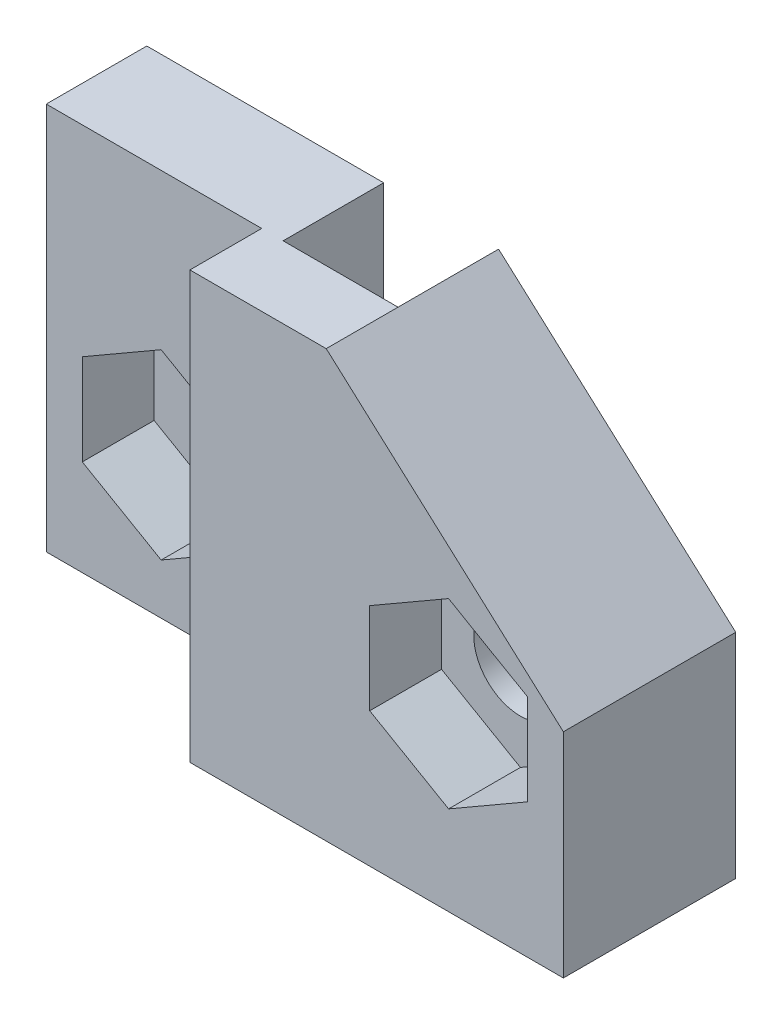
SolidWorks part; units mm, degrees
ref_plane "Alzado" through (0, 0, 0) normal (0, 0, 1) x (1, 0, 0)
ref_plane "Planta" through (0, 0, 0) normal (0, 1, 0) x (1, 0, 0)
ref_plane "Vista lateral" through (0, 0, 0) normal (1, 0, 0) x (0, 0, -1)
sketch "Croquis1" plane through (0, 0, 0) normal (0, 0, 1) x (1, 0, 0)
  line L0 (168.7324, -66.6486) -> (161.2324, -66.6486)
  line L1 (88.7324, -66.6486) -> (168.7324, -66.6486) construction
  line L2 (168.7324, -66.6486) -> (168.7324, -80.1486)
  line L4 (161.2324, -80.1486) -> (161.2324, -66.6486)
  line L5 (168.7324, -80.1486) -> (168.7324, -81.4936)
  line L7 (161.2324, -80.1486) -> (167.3874, -80.1486)
  line L8 (168.7324, -81.4936) -> (167.3874, -80.1486)
  circle A0 centre (165.2324, -75.2236) radius 1.5
  dimension "D1" = 3
  dimension "D2" = 161.2324
  dimension "D3" = 167.3874
  dimension "D4" = 81.4936
extrude "Saliente-Extruir1" add sketch "Croquis1" along normal blind 3.5
sketch "Croquis3" plane through (0, 0, 3.5) normal (0, 0, 1) x (1, 0, 0)
  line L1 (168.7324, -81.4936) -> (181.7324, -81.4936)
  line L2 (181.7324, -81.4936) -> (181.7324, -74.0711)
  line L3 (168.7324, -66.6486) -> (168.7324, -81.4936)
  line L4 (168.7324, -66.6486) -> (169.4777, -66.6486)
  line L5 (173.4777, -66.6486) -> (181.7324, -74.0711)
  line L7 (173.4777, -75.2236) -> (169.4777, -75.2236)
  line L8 (173.4777, -75.2236) -> (173.4777, -66.6486)
  line L9 (169.4777, -75.2236) -> (169.4777, -66.6486)
  line L10 (161.2324, -66.6486) -> (161.2324, -80.1486) construction
  line L11 (168.7324, -66.6486) -> (161.2324, -66.6486) construction
  circle A0 centre (177.7371, -75.2236) radius 1.625
  dimension "D1" = 3.25
  dimension "D2" = 8.2453
  dimension "D3" = 12.2453
  dimension "D4" = 16.5047
  dimension "D5" = 20.5
  dimension "D6" = 7.4225
  dimension "D7" = 8.575
extrude "Saliente-Extruir2" add sketch "Croquis3" along normal blind 2.5 and the other way blind 3.5
sketch "Croquis4" plane through (0, 0, 6) normal (0, 0, 1) x (1, 0, 0)
  line L9 (177.7371, -78.3936) -> (180.4824, -76.8086)
  line L10 (180.4824, -76.8086) -> (180.4824, -73.6386)
  line L11 (180.4824, -73.6386) -> (177.7371, -72.0536)
  line L12 (177.7371, -72.0536) -> (174.9918, -73.6386)
  line L13 (174.9918, -73.6386) -> (174.9918, -76.8086)
  line L14 (174.9918, -76.8086) -> (177.7371, -78.3936)
  circle A0 centre (177.7371, -75.2236) radius 2.7453 construction
  dimension "D1" = 5.4906
extrude "Cortar-Extruir1" cut sketch "Croquis4" against normal blind 2.5
sketch "Croquis5" plane through (0, 0, 3.5) normal (0, 0, 1) x (1, 0, 0)
  line L1 (165.2324, -78.3936) -> (167.9777, -76.8086)
  line L2 (167.9777, -76.8086) -> (167.9777, -73.6386)
  line L3 (167.9777, -73.6386) -> (165.2324, -72.0536)
  line L4 (165.2324, -72.0536) -> (162.4871, -73.6386)
  line L5 (162.4871, -73.6386) -> (162.4871, -76.8086)
  line L6 (162.4871, -76.8086) -> (165.2324, -78.3936)
  circle A0 centre (165.2324, -75.2236) radius 2.7453 construction
  dimension "D1" = 5.4906
extrude "Cortar-Extruir2" cut sketch "Croquis5" against normal blind 2.5
sketch "Croquis6" plane through (0, 0, 6) normal (0, 0, 1) x (1, 0, 0)
  line L1 (169.4777, -66.6486) -> (173.4777, -66.6486)
  line L2 (169.4777, -66.6486) -> (169.4777, -75.2236)
  line L3 (169.4777, -75.2236) -> (173.4777, -75.2236)
  line L4 (173.4777, -66.6486) -> (173.4777, -75.2236)
extrude "Saliente-Extruir4" add sketch "Croquis6" against normal blind 2.5
